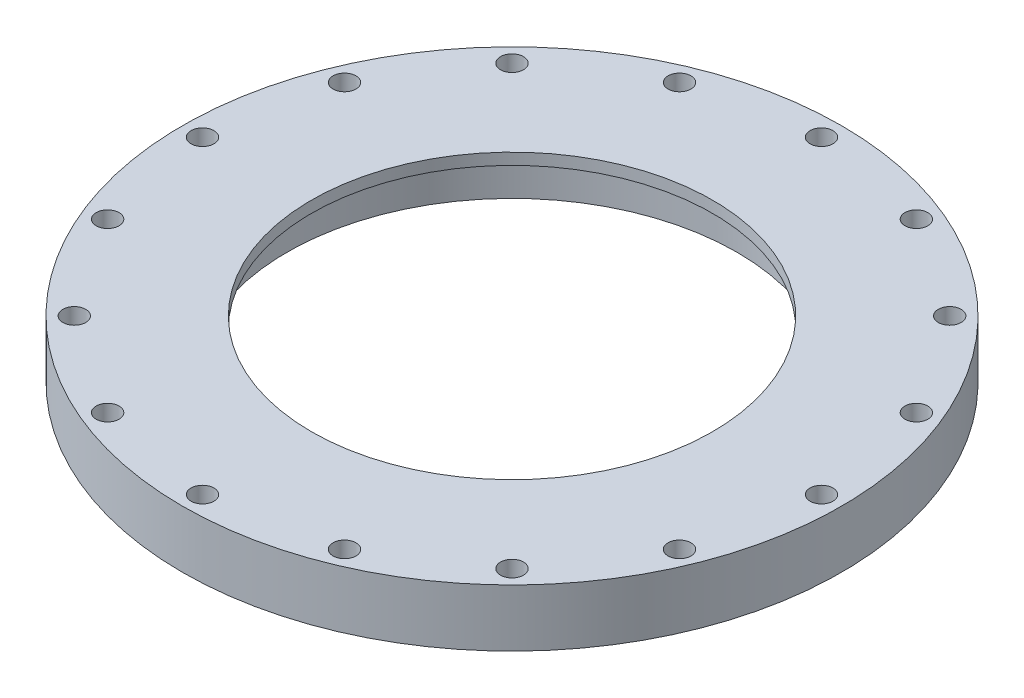
SolidWorks part; units mm, degrees
ref_plane "Front Plane" through (0, 0, 0) normal (0, 0, 1) x (1, 0, 0)
ref_plane "Top Plane" through (0, 0, 0) normal (0, 1, 0) x (1, 0, 0)
ref_plane "Right Plane" through (0, 0, 0) normal (1, 0, 0) x (0, 0, -1)
sketch "Sketch1" plane through (0, 0, 0) normal (0, 1, 0) x (1, 0, 0)
  circle A0 centre (0, 0) radius 57.5
  circle A1 centre (0, 0) radius 39.25
  dimension "D1" = 78.5
  dimension "D2" = 115
extrude "Boss-Extrude1" add sketch "Sketch1" along normal blind 8
sketch "Sketch3" plane through (0, 8, 0) normal (0, 1, 0) x (1, 0, 0)
  circle A0 centre (0, 0) radius 57.5
  circle A1 centre (0, 0) radius 35
  dimension "D1" = 70
extrude "Boss-Extrude2" add sketch "Sketch3" along normal blind 2
sketch "Sketch2" plane through (0, 10, 0) normal (0, 1, 0) x (1, 0, 0)
  circle A0 centre (0, 0) radius 54 construction
  circle A1 centre (0, 54) radius 2
  circle A2 centre (20.6649, 49.8895) radius 2
  circle A3 centre (38.1838, 38.1838) radius 2
  circle A4 centre (49.8895, 20.6649) radius 2
  circle A5 centre (54, 0) radius 2
  circle A6 centre (49.8895, -20.6649) radius 2
  circle A7 centre (38.1838, -38.1838) radius 2
  circle A8 centre (20.6649, -49.8895) radius 2
  circle A9 centre (0, -54) radius 2
  circle A10 centre (-20.6649, -49.8895) radius 2
  circle A11 centre (-38.1838, -38.1838) radius 2
  circle A12 centre (-49.8895, -20.6649) radius 2
  circle A13 centre (-54, 0) radius 2
  circle A14 centre (-49.8895, 20.6649) radius 2
  circle A15 centre (-38.1838, 38.1838) radius 2
  circle A16 centre (-20.6649, 49.8895) radius 2
  point P37 (0, 0)
  dimension "D1" = 108
  dimension "D2" = 4
  dimension "D3" = 16
extrude "Cut-Extrude1" cut sketch "Sketch2" against normal blind 25
